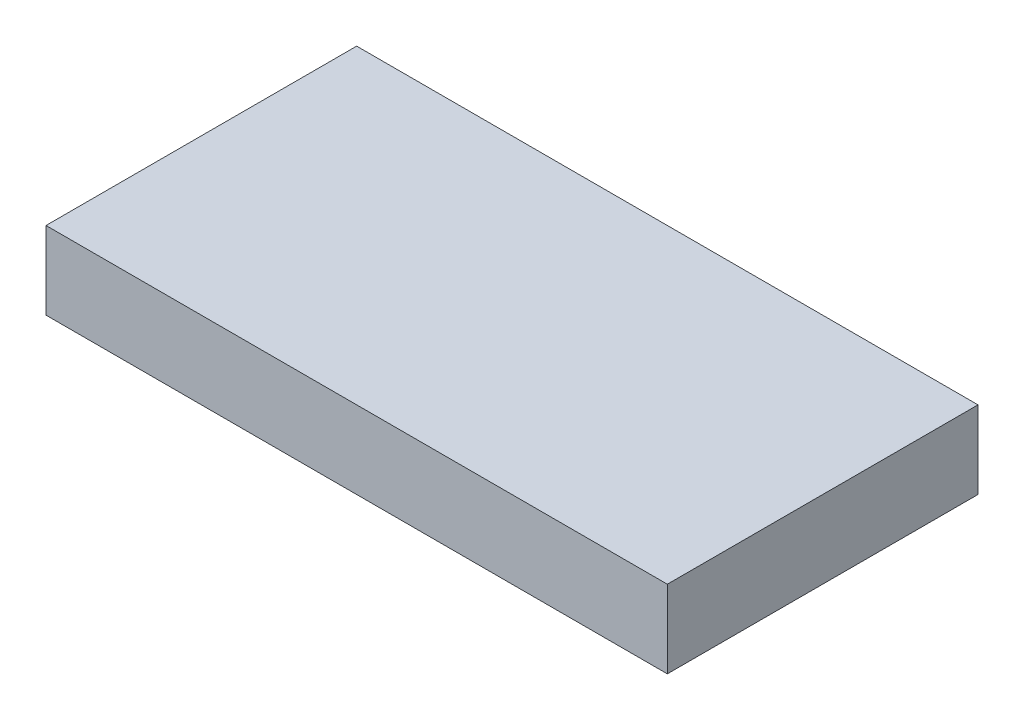
SolidWorks part; units mm, degrees
ref_plane "Front" through (0, 0, 0) normal (0, 0, 1) x (1, 0, 0)
ref_plane "Top" through (0, 0, 0) normal (0, 1, 0) x (1, 0, 0)
ref_plane "Right" through (0, 0, 0) normal (1, 0, 0) x (0, 0, -1)
sketch "Sketch1" plane through (0, 0, 0) normal (0, 1, 0) x (1, 0, 0)
  line L1 (-20, 10) -> (20, 10)
  line L2 (-20, 10) -> (-20, -10)
  line L3 (-20, -10) -> (20, -10)
  line L4 (20, 10) -> (20, -10)
  line L5 (-20, 10) -> (20, -10) construction
  line L6 (-20, -10) -> (20, 10) construction
  point P0 (0, 0)
  dimension "D1" = 40
  dimension "D2" = 20
extrude "Boss-Extrude1" add sketch "Sketch1" along normal blind 5
